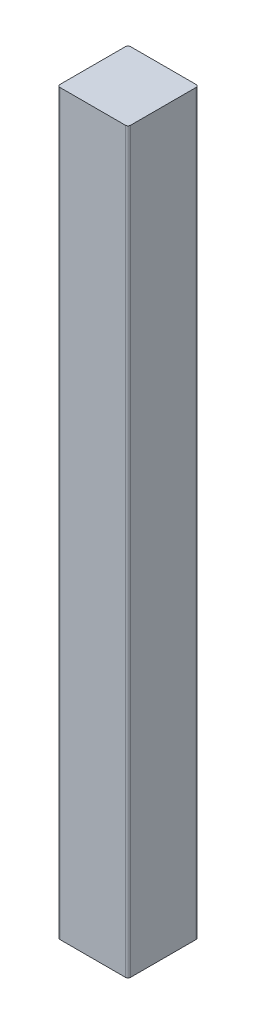
SolidWorks part; units mm, degrees
material "Pine"
ref_plane "Front Plane" through (0, 0, 0) normal (0, 0, 1) x (1, 0, 0)
ref_plane "Top Plane" through (0, 0, 0) normal (0, 1, 0) x (1, 0, 0)
ref_plane "Right Plane" through (0, 0, 0) normal (1, 0, 0) x (0, 0, -1)
sketch "Sketch1" plane through (0, 0, 0) normal (0, 1, 0) x (1, 0, 0)
  line L1 (-44.45, 44.45) -> (44.45, 44.45)
  line L2 (-44.45, 44.45) -> (-44.45, -44.45)
  line L3 (-44.45, -44.45) -> (44.45, -44.45)
  line L4 (44.45, 44.45) -> (44.45, -44.45)
  line L5 (-44.45, 44.45) -> (44.45, -44.45) construction
  line L6 (-44.45, -44.45) -> (44.45, 44.45) construction
  point P0 (0, 0)
  dimension "D1" = 88.9
extrude "Boss-Extrude1" add sketch "Sketch1" along normal blind 928.6875
fillet "Fillet1" radius 3.175 4 edges at (-44.45, 464.3438, 44.45) (-44.45, 464.3438, -44.45) (44.45, 464.3438, -44.45) (44.45, 464.3438, 44.45)
